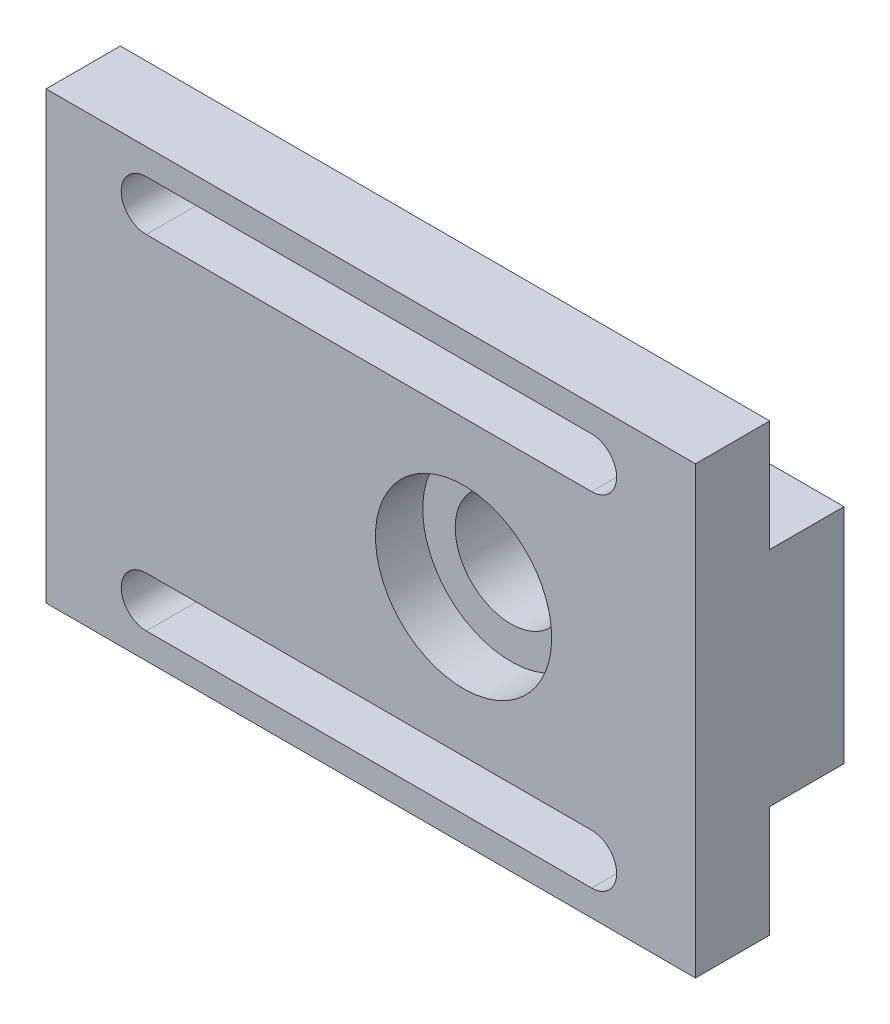
SolidWorks part; units mm, degrees
material "SKD11淬火HRC56-60"
ref_plane "前基準面" through (0, 0, 0) normal (0, 0, 1) x (1, 0, 0)
ref_plane "上基準面" through (0, 0, 0) normal (0, 1, 0) x (1, 0, 0)
ref_plane "右基準面" through (0, 0, 0) normal (1, 0, 0) x (0, 0, -1)
sketch "草图1" plane through (0, 0, 0) normal (0, 0, 1) x (1, 0, 0)
  line L1 (0, 0) -> (70, 0)
  line L2 (0, 0) -> (0, 48)
  line L3 (0, 48) -> (70, 48)
  line L4 (70, 0) -> (70, 48)
  dimension "D1" = 70
  dimension "D2" = 48
extrude "凸台-拉伸1" add sketch "草图1" along normal blind 8
sketch "草图2" plane through (0, 0, 0) normal (0, 0, -1) x (-1, 0, 0)
  line L0 (-70, 0) -> (-70, 48) construction
  line L1 (-70, 12) -> (0, 12)
  line L2 (-70, 12) -> (-70, 36)
  line L3 (-70, 36) -> (0, 36)
  line L4 (0, 12) -> (0, 36)
  line L5 (0, 48) -> (0, 0) construction
  line L6 (0, 24) -> (-70, 24) construction
  dimension "D1" = 24
extrude "凸台-拉伸2" add sketch "草图2" along normal blind 8
sketch "草图3" plane through (0, 0, -8) normal (0, 0, -1) x (-1, 0, 0)
  line L0 (-70, 24) -> (0, 24) construction
  line L1 (-70, 36) -> (-70, 12) construction
  line L2 (0, 12) -> (0, 36) construction
  circle A0 centre (-45, 24) radius 6
  dimension "D1" = 12
  dimension "D2" = 25
extrude "切除-拉伸1" cut sketch "草图3" against normal through all
sketch "草图6" plane through (0, 0, -8) normal (0, 0, -1) x (-1, 0, 0)
  circle A0 centre (-45, 24) radius 9.5
  dimension "D1" = 19
extrude "切除-拉伸4" cut sketch "草图6" against normal blind 5
sketch "草图7" plane through (0, 0, 8) normal (0, 0, 1) x (1, 0, 0)
  circle A0 centre (45, 24) radius 9.5
  dimension "D1" = 19
extrude "切除-拉伸5" cut sketch "草图7" against normal blind 5.1
hole_wizard "M4 螺纹孔1" positions "草图9" profile "草图8" tap size "M4" standard "ISO"
sketch "草图9" plane through (0, 0, -8) normal (0, 0, -1) x (-1, 0, 0)
  line L0 (0, 24) -> (-70, 24) construction
  line L1 (0, 12) -> (0, 36) construction
  line L2 (-70, 36) -> (-70, 12) construction
  line L3 (-45, 33.5) -> (-45, 14.5) construction
  circle A0 centre (-45, 24) radius 9.5 construction
  point P0 (-57.5, 24)
  point P1 (-32.5, 24)
  dimension "D1" = 25
sketch "草图8" plane through (57.5, 24, -8) normal (1, 0, 0) x (0, 1, 0)
  line L0 (0, 0) -> (0, 11.0914)
  line L1 (0, 11.0914) -> (1.65, 10.1)
  line L2 (1.65, 10.1) -> (1.65, 0)
  line L5 (1.65, 0) -> (0, 0)
  line L10 (0, 11.0914) -> (-1.65, 10.1) construction
  line L11 (0, -6.35) -> (0, 107.95) construction
  dimension "螺纹孔钻头直径" = 3.3
  dimension "螺纹孔钻头深度" = 10.1
  dimension "导头角度" = 118
cosmetic thread "孔螺蚊线1" parameters "D1"=8, "D2"=4
cosmetic thread "孔螺蚊线2" parameters "D1"=8, "D2"=4
sketch "草图10" plane through (0, 0, 8) normal (0, 0, 1) x (1, 0, 0)
  line L0 (10.8005, 42.5) -> (58.8005, 42.5) construction
  line L1 (10.8005, 45.2) -> (58.8005, 45.2)
  line L2 (10.8005, 39.8) -> (58.8005, 39.8)
  line L3 (35, 48) -> (35, 0) construction
  line L4 (70, 48) -> (0, 48) construction
  line L5 (0, 0) -> (70, 0) construction
  line L6 (0, 24) -> (70, 24) construction
  line L7 (0, 48) -> (0, 0) construction
  line L8 (70, 0) -> (70, 48) construction
  line L9 (10.8005, 5.5) -> (58.8005, 5.5) construction
  line L10 (10.8005, 2.8) -> (58.8005, 2.8)
  line L11 (10.8005, 8.2) -> (58.8005, 8.2)
  arc A0 (10.8005, 45.2) -> (10.8005, 39.8) centre (10.8005, 42.5) ccw
  arc A1 (58.8005, 39.8) -> (58.8005, 45.2) centre (58.8005, 42.5) ccw
  arc A2 (10.8005, 2.8) -> (10.8005, 8.2) centre (10.8005, 5.5) cw
  arc A3 (58.8005, 8.2) -> (58.8005, 2.8) centre (58.8005, 5.5) cw
  point P2 (34.8005, 42.5)
  point P21 (34.8005, 5.5)
  dimension "D1" = 5.4
  dimension "D2" = 48
  dimension "D3" = 5.5
extrude "切除-拉伸6" cut sketch "草图10" against normal through all
